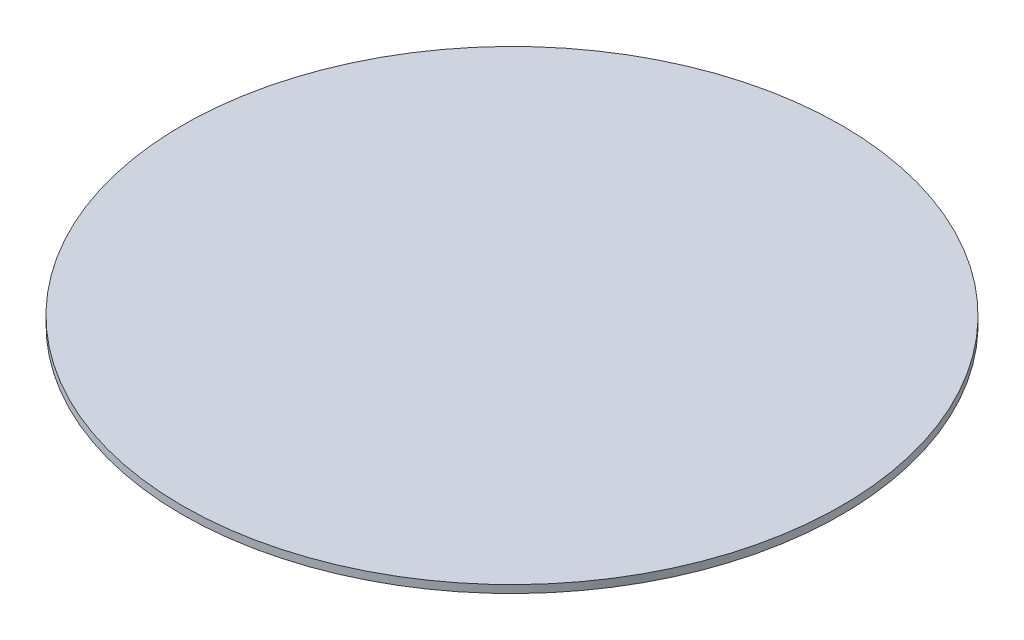
SolidWorks part; units mm, degrees
ref_plane "Front Plane" through (0, 0, 0) normal (0, 0, 1) x (1, 0, 0)
ref_plane "Top Plane" through (0, 0, 0) normal (0, 1, 0) x (1, 0, 0)
ref_plane "Right Plane" through (0, 0, 0) normal (1, 0, 0) x (0, 0, -1)
sketch "Sketch1" plane through (0, 0, 0) normal (0, 1, 0) x (1, 0, 0)
  circle A0 centre (0, 0) radius 34
  dimension "D1" = 68
extrude "Boss-Extrude1" add sketch "Sketch1" along normal blind 0.8
